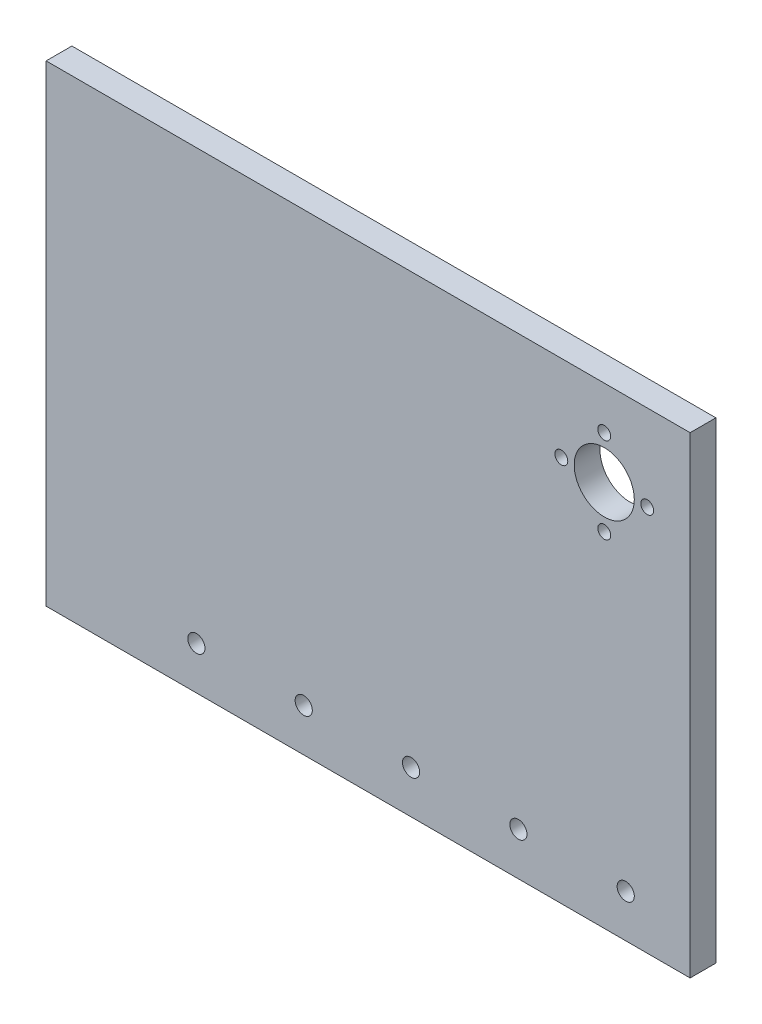
SolidWorks part; units mm, degrees
ref_plane "Plan de face" through (0, 0, 0) normal (0, 0, 1) x (1, 0, 0)
ref_plane "Plan de dessus" through (0, 0, 0) normal (0, 1, 0) x (1, 0, 0)
ref_plane "Plan de droite" through (0, 0, 0) normal (1, 0, 0) x (0, 0, -1)
sketch "Esquisse1" plane through (0, 0, 0) normal (0, 0, 1) x (1, 0, 0)
  line L1 (0, 0) -> (150, 0)
  line L2 (0, 0) -> (0, 110)
  line L3 (0, 110) -> (150, 110)
  line L4 (150, 0) -> (150, 110)
  dimension "D1" = 110
  dimension "D2" = 150
extrude "Boss.-Extru.1" add sketch "Esquisse1" along normal blind 6
sketch "Esquisse2" plane through (0, 0, 6) normal (0, 0, 1) x (1, 0, 0)
  line L0 (85, 0) -> (85, 108.7105) construction
  line L1 (0, 0) -> (150, 0) construction
  line L2 (0, 110) -> (0, 0) construction
  line L3 (135, 10) -> (110, 10) construction
  line L4 (110, 10) -> (85, 10) construction
  line L5 (35, 10) -> (60, 10) construction
  circle A0 centre (110, 10) radius 2
  circle A1 centre (135, 10) radius 2
  circle A2 centre (35, 10) radius 2
  circle A3 centre (60, 10) radius 2
  circle A4 centre (85, 10) radius 2
  point P4 (0, 0)
  point P5 (58.6433, 108.7105)
  point P16 (0, 0)
  dimension "D2" = 4
  dimension "D3" = 25
  dimension "D4" = 25
  dimension "D1" = 10
  dimension "D5" = 85
extrude "Enlèv. mat.-Extru.1" cut sketch "Esquisse2" against normal through all
sketch "Esquisse3" plane through (0, 0, 6) normal (0, 0, 1) x (1, 0, 0)
  line L0 (0, 0) -> (150, 0) construction
  circle A0 centre (130, 90) radius 7
  circle A1 centre (85, 10) radius 2 construction
  dimension "D1" = 14
  dimension "D2" = 90
  dimension "D3" = 45
extrude "Enlèv. mat.-Extru.2" cut sketch "Esquisse3" against normal through all
sketch "Esquisse4" plane through (0, 0, 6) normal (0, 0, 1) x (1, 0, 0)
  line L0 (130, 90) -> (130, 100) construction
  circle A0 centre (130, 100) radius 1.5
  circle A1 centre (140, 90) radius 1.5
  circle A2 centre (130, 80) radius 1.5
  circle A3 centre (120, 90) radius 1.5
  point P12 (130, 90)
  dimension "D1" = 3
  dimension "D2" = 10
  dimension "D3" = 4
extrude "Enlèv. mat.-Extru.3" cut sketch "Esquisse4" against normal up to vertex (6 mm away)
